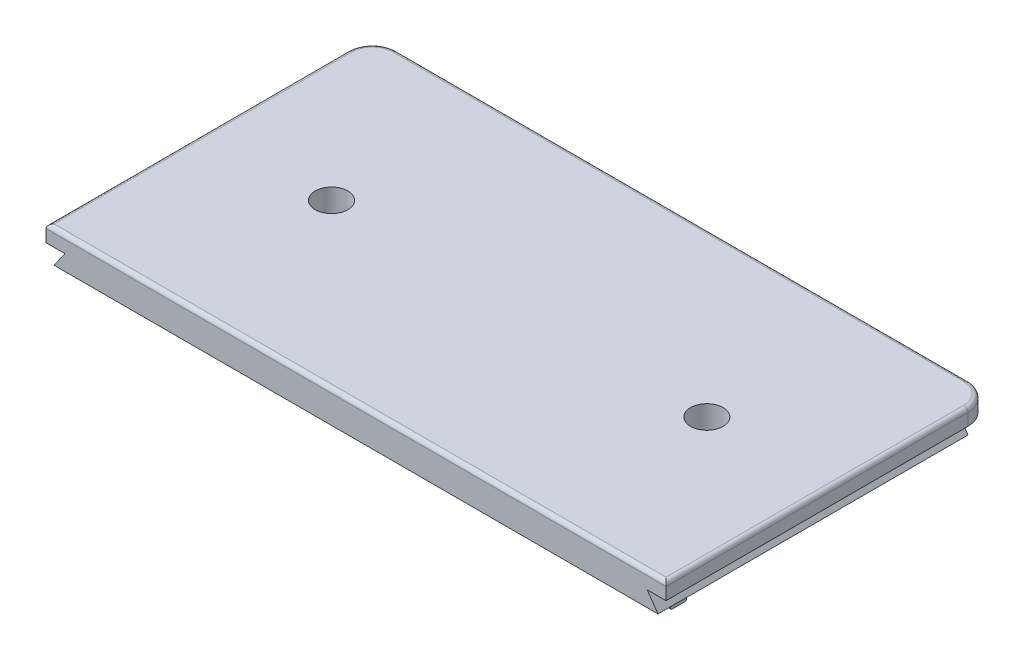
SolidWorks part; units mm, degrees
ref_plane "Front Plane" through (0, 0, 0) normal (0, 0, 1) x (1, 0, 0)
ref_plane "Top Plane" through (0, 0, 0) normal (0, 1, 0) x (1, 0, 0)
ref_plane "Right Plane" through (0, 0, 0) normal (1, 0, 0) x (0, 0, -1)
sketch "Sketch1" plane through (0, 0, 0) normal (0, 0, 1) x (1, 0, 0)
  line L0 (-14.5, 22) -> (-37.4004, 22) construction
  line L1 (37.4004, 22) -> (-37.4004, 22) construction
  line L3 (36, 24) -> (37.4004, 22) construction
  line L4 (36, 24) -> (37.4004, 22) construction
  line L5 (-37.4004, 22) -> (-36, 24) construction
  line L6 (-37.4004, 22) -> (-36, 24) construction
  line L7 (35.7558, 24) -> (37.0162, 22.2)
  line L8 (37.0162, 22.2) -> (-37.0162, 22.2)
  line L9 (-37.0162, 22.2) -> (-35.7558, 24)
  line L10 (35.8362, 23.8853) -> (37.0162, 22.2) construction
  line L11 (-36, 24) -> (36, 24) construction
  line L12 (-37.0162, 22.2) -> (-35.8362, 23.8853) construction
  line L13 (-35.7558, 24) -> (-35.7558, 24.1)
  line L14 (-35.7558, 24.1) -> (-38, 24.1)
  line L15 (-38, 24.1) -> (-38, 26.1)
  line L16 (-38, 26.1) -> (38, 26.1)
  line L17 (-38, 24) -> (-38, 0.5) construction
  line L18 (0, 2) -> (0, 26.1) construction
  line L19 (36, 2) -> (-36, 2) construction
  line L20 (35.7558, 24) -> (35.7558, 24.1)
  line L21 (35.7558, 24.1) -> (38, 24.1)
  line L22 (38, 24.1) -> (38, 26.1)
  dimension "D2" = 0.1
  dimension "D3" = 2
  dimension "D1" = 0.2
extrude "Boss-Extrude1" add sketch "Sketch1" against normal up to surface (38 mm away) contours L16 L22 L21 L20 L7 L8 L9 L13 L14 L15
sketch "Sketch2" plane through (0, 0, -38) normal (0, 0, -1) x (-1, 0, 0)
  line L1 (-38, 24.1) -> (38, 24.1)
  line L2 (-38, 24.1) -> (-38, 26.1)
  line L3 (-38, 26.1) -> (38, 26.1)
  line L4 (38, 24.1) -> (38, 26.1)
extrude "Boss-Extrude2" add sketch "Sketch2" along normal up to surface (2 mm away)
fillet "Fillet1" radius 3 2 edges at (-38, 25.1, -40) (38, 25.1, -40)
fillet "Fillet2" radius 0.5 6 edges at (37.1213, 26.1, -39.1213) (38, 26.1, -18.5) (0, 26.1, 0) (-38, 26.1, -18.5) (-37.1213, 26.1, -39.1213) (0, 26.1, -40)
sketch "Sketch3" plane through (0, 26.1, 0) normal (0, 1, 0) x (1, 0, 0)
  line L0 (0, 0) -> (0, 40) construction
  line L1 (-35, 40) -> (35, 40) construction
  line L2 (38, 20) -> (-38, 20) construction
  line L3 (-38, 0) -> (-38, 37) construction
  line L4 (38, 37) -> (38, 0) construction
  circle A0 centre (-23, 20) radius 2
  circle A1 centre (23, 20) radius 2
  point P9 (0, 20)
  dimension "D1" = 4
  dimension "D2" = 15
extrude "Cut-Extrude1" cut sketch "Sketch3" against normal up to next
sketch "Sketch4" plane through (0, 22.2, 0) normal (0, -1, 0) x (1, 0, 0)
  line L0 (37.0162, -38) -> (37.0162, 0) construction
  line L1 (37.0162, -1.5) -> (-37.0162, -1.5)
  line L2 (37.0162, -1.5) -> (37.0162, -3.5)
  line L3 (37.0162, -3.5) -> (-37.0162, -3.5)
  line L4 (-37.0162, -1.5) -> (-37.0162, -3.5)
  line L5 (37.4004, -1.5) -> (14.5, -1.5) construction
  line L6 (-37.0162, -38) -> (-37.0162, 0) construction
  dimension "D1" = 2
extrude "Boss-Extrude3" add sketch "Sketch4" along normal blind 0.35
fillet "Fillet3" radius 0.25 2 edges at (0, 21.85, -3.5) (0, 21.85, -1.5)
